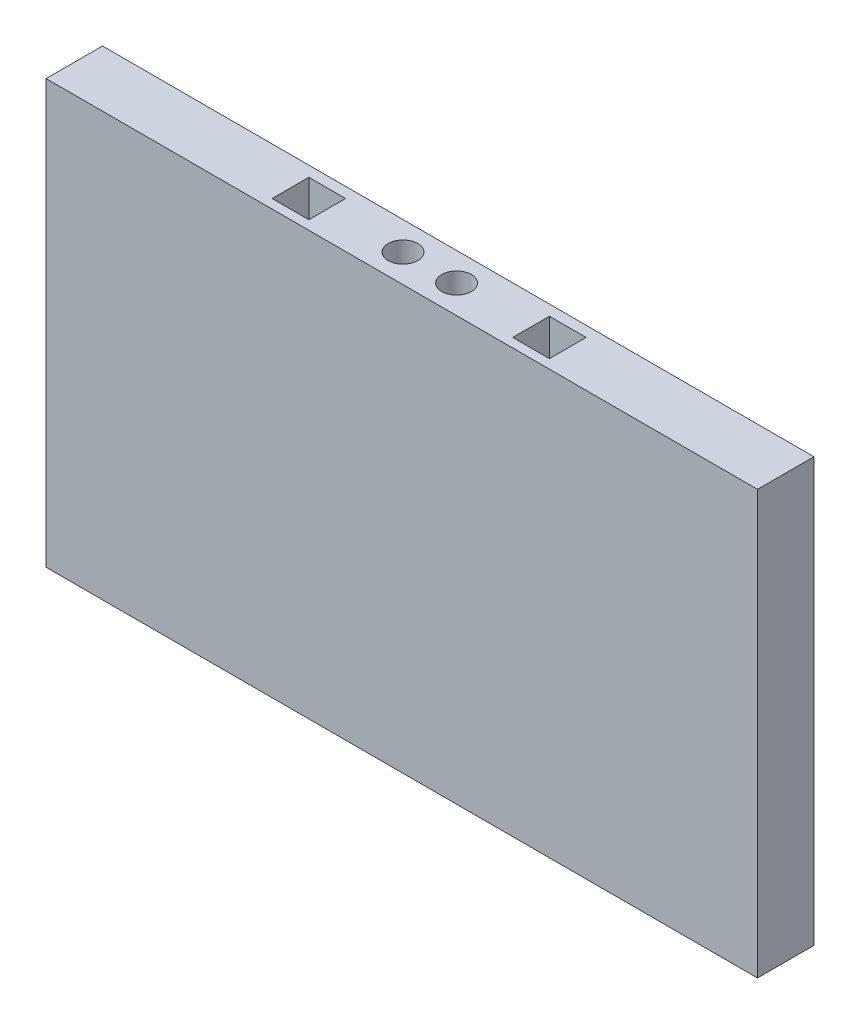
SolidWorks part; units mm, degrees
ref_plane "Front Plane" through (0, 0, 0) normal (0, 0, 1) x (1, 0, 0)
ref_plane "Top Plane" through (0, 0, 0) normal (0, 1, 0) x (1, 0, 0)
ref_plane "Right Plane" through (0, 0, 0) normal (1, 0, 0) x (0, 0, -1)
sketch "Sketch1" plane through (0, 0, 0) normal (0, 0, 1) x (1, 0, 0)
  line L1 (-107.8214, 92.0904) -> (-7.8214, 92.0904)
  line L3 (-107.8214, 44.0904) -> (-7.8214, 44.0904)
  line L5 (-107.8214, 92.0904) -> (-182.8214, 92.0904)
  line L7 (-107.8214, 44.0904) -> (-182.8214, 44.0904)
  line L8 (-182.8214, 92.0904) -> (-182.8214, 44.0904)
  line L9 (-7.8214, 92.0904) -> (117.1786, 92.0904)
  line L11 (-7.8214, 44.0904) -> (117.1786, 44.0904)
  line L12 (117.1786, 92.0904) -> (117.1786, 44.0904)
  dimension "D1" = 48
  dimension "D2" = 100
  dimension "D3" = 75
  dimension "D4" = 125
extrude "Boss-Extrude1" add sketch "Sketch1" along normal blind 20
sketch "Sketch5" plane through (0, 92.0904, 0) normal (0, 1, 0) x (1, 0, 0)
  line L0 (-182.8214, -20) -> (-157.8214, -20) construction
  line L2 (117.1786, -20) -> (-182.8214, -20) construction
  line L3 (-157.8214, -20) -> (-57.8214, -20) construction
  line L4 (-57.8214, -20) -> (-66.3214, -20) construction
  line L5 (-66.3214, -20) -> (-66.3214, -16) construction
  line L6 (-66.3214, -16) -> (-66.3214, -10) construction
  line L7 (-66.3214, -10) -> (-47.3214, -10) construction
  circle A0 centre (-66.3214, -10) radius 5.25
  circle A1 centre (-47.3214, -10) radius 5.25
extrude "Cut-Extrude4" cut sketch "Sketch5" against normal blind 20
sketch "Sketch6" plane through (0, 92.0904, 0) normal (0, 1, 0) x (1, 0, 0)
  line L0 (-182.8214, 0) -> (-105.6914, 0) construction
  line L1 (117.1786, 0) -> (-182.8214, 0) construction
  line L2 (-105.6914, 0) -> (-105.6914, -4) construction
  line L3 (-105.9414, -3.75) -> (-92.9414, -3.75)
  line L8 (-92.9414, -3.75) -> (-92.9414, -16.75)
  line L9 (-105.9414, -16.75) -> (-92.9414, -16.75)
  line L10 (-105.9414, -3.75) -> (-105.9414, -16.75)
extrude "Cut-Extrude5" cut sketch "Sketch6" against normal blind 15.5
sketch "Sketch7" plane through (0, 92.0904, 0) normal (0, 1, 0) x (1, 0, 0)
  line L0 (117.1786, 0) -> (-7.9138, 0) construction
  line L1 (117.1786, 0) -> (-182.8214, 0) construction
  line L2 (-7.9138, 0) -> (-7.9138, -4) construction
  line L3 (-7.6638, -3.75) -> (-20.6638, -3.75)
  line L8 (-20.6638, -3.75) -> (-20.6638, -16.75)
  line L9 (-7.6638, -16.75) -> (-20.6638, -16.75)
  line L10 (-7.6638, -3.75) -> (-7.6638, -16.75)
extrude "Cut-Extrude6" cut sketch "Sketch7" against normal blind 15.5
sketch "Sketch8" plane through (0, 0, 20) normal (0, 0, 1) x (1, 0, 0)
  line L0 (117.1786, 44.0904) -> (117.1786, 92.0904) construction
  line L1 (-182.8214, 44.0904) -> (117.1786, 44.0904)
  line L2 (-182.8214, 44.0904) -> (-182.8214, -57.9096)
  line L3 (-182.8214, -57.9096) -> (117.1786, -57.9096)
  line L4 (117.1786, 44.0904) -> (117.1786, -57.9096)
  dimension "D1" = 150
extrude "Boss-Extrude2" add sketch "Sketch8" against normal up to surface (20 mm away) up to face at (-32.8214, 68.0904, 0)
sketch "Sketch9" plane through (0, 92.0904, 0) normal (0, 1, 0) x (1, 0, 0)
  line L1 (-105.9414, -3.75) -> (-105.9414, -16.75) construction
  line L2 (-7.6638, -3.75) -> (-7.6638, -16.75) construction
  line L4 (117.1786, 0) -> (-182.8214, 0) construction
  line L5 (69.3362, 0) -> (69.3362, -20) construction
  line L6 (117.1786, -20) -> (-182.8214, -20) construction
  line L8 (117.1786, -20) -> (69.3362, -20)
  line L9 (117.1786, -20) -> (117.1786, 0)
  line L10 (117.1786, 0) -> (69.3362, 0)
  line L11 (69.3362, -20) -> (69.3362, 0)
  dimension "D1" = 77
extrude "Cut-Extrude7" cut sketch "Sketch9" against normal up to vertex
